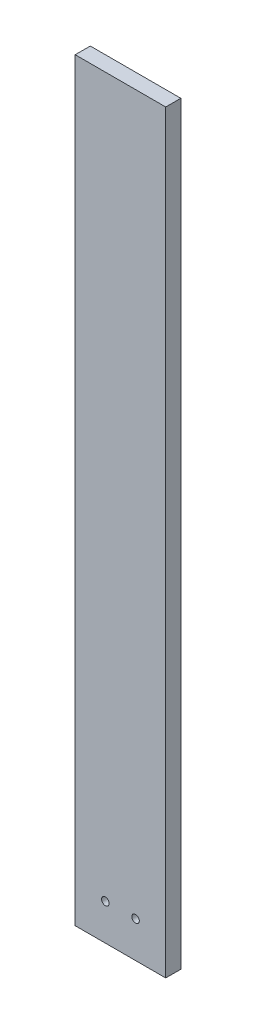
SolidWorks part; units mm, degrees
material "Balsa"
ref_plane "Plan de face" through (0, 0, 0) normal (0, 0, 1) x (1, 0, 0)
ref_plane "Plan de dessus" through (0, 0, 0) normal (0, 1, 0) x (1, 0, 0)
ref_plane "Plan de droite" through (0, 0, 0) normal (1, 0, 0) x (0, 0, -1)
sketch "Sketch1" plane through (0, 0, 0) normal (0, 0, 1) x (1, 0, 0)
  line L1 (-30, -250) -> (30, -250)
  line L2 (-30, -250) -> (-30, 250)
  line L3 (-30, 250) -> (30, 250)
  line L4 (30, -250) -> (30, 250)
  line L5 (-30, -250) -> (30, 250) construction
  line L6 (-30, 250) -> (30, -250) construction
  point P0 (0, 0)
  dimension "D1" = 60
  dimension "D2" = 500
extrude "Boss-Extrude1" add sketch "Sketch1" along normal blind 10
sketch "Sketch2" plane through (0, 0, 0) normal (0, 0, -1) x (-1, 0, 0)
  line L0 (0, 35.0584) -> (0, -130.1565) construction
  line L2 (30, -250) -> (-30, -250) construction
  circle A0 centre (10, -226) radius 2.5
  circle A1 centre (-10, -226) radius 2.5
  dimension "D1" = 5
  dimension "D2" = 10
  dimension "D3" = 24
extrude "Cut-Extrude1" cut sketch "Sketch2" against normal through all
